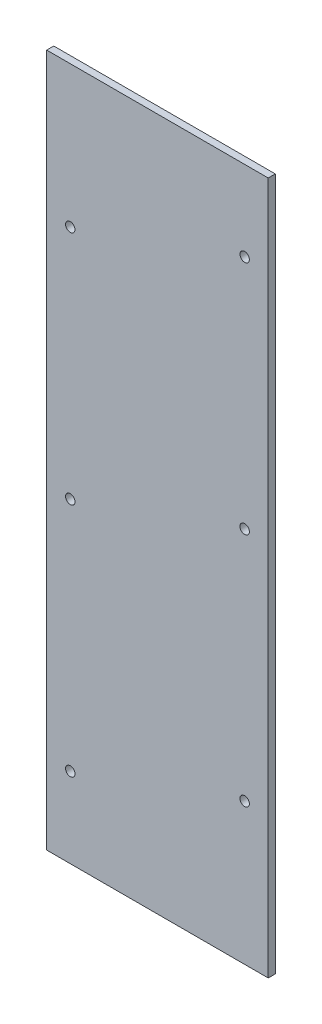
SolidWorks part; units mm, degrees
ref_plane "Front Plane" through (0, 0, 0) normal (0, 0, 1) x (1, 0, 0)
ref_plane "Top Plane" through (0, 0, 0) normal (0, 1, 0) x (1, 0, 0)
ref_plane "Right Plane" through (0, 0, 0) normal (1, 0, 0) x (0, 0, -1)
sketch "Sketch1" plane through (0, 0, 0) normal (0, 0, 1) x (1, 0, 0)
  line L1 (-47, -147) -> (47, -147)
  line L2 (-47, -147) -> (-47, 147)
  line L3 (-47, 147) -> (47, 147)
  line L4 (47, -147) -> (47, 147)
  line L5 (-47, -147) -> (47, 147) construction
  line L6 (-47, 147) -> (47, -147) construction
  point P0 (0, 0)
  dimension "D1" = 294
  dimension "D2" = 94
extrude "Boss-Extrude1" add sketch "Sketch1" along normal blind 3
sketch "Sketch2" plane through (0, 0, 3) normal (0, 0, 1) x (1, 0, 0)
  line L0 (-27, 147) -> (-27, -147) construction
  line L1 (27, -147) -> (27, 147) construction
  line L2 (-47, 147) -> (-27, 147) construction
  line L3 (-37, 147) -> (-37, -147) construction
  line L4 (47, -147) -> (47, 147)
  line L5 (47, 147) -> (-47, 147)
  line L6 (-47, 147) -> (-47, -147)
  line L7 (-47, -147) -> (47, -147)
  line L8 (47, -147) -> (47, 147) construction
  line L9 (47, 147) -> (-47, 147) construction
  line L10 (-47, 147) -> (-47, -147) construction
  line L11 (-47, -147) -> (47, -147) construction
  line L12 (27, 147) -> (47, 147) construction
  line L13 (47, 147) -> (27, 147)
  line L14 (37, 147) -> (37, -147) construction
  circle A0 centre (-37, -13) radius 2
  circle A1 centre (-37, 87) radius 2
  circle A2 centre (-37, -113) radius 2
  circle A3 centre (37, -87) radius 2
  circle A4 centre (37, 13) radius 2
  circle A5 centre (37, 113) radius 2
  dimension "D4" = 4
  dimension "D5" = 4
  dimension "D7" = 4
  dimension "D9" = 4
  dimension "D10" = 4
  dimension "D11" = 4
  dimension "D3" = 100
  dimension "D6" = 100
  dimension "D8" = 60
  dimension "D12" = 60
  dimension "D13" = 100
  dimension "D14" = 100
  dimension "D1" = 0
  dimension "D2" = 20
extrude "Cut-Extrude1" cut sketch "Sketch2" against normal blind 3 contours A2 | A3 | A4 | A0 | A1 | A5
